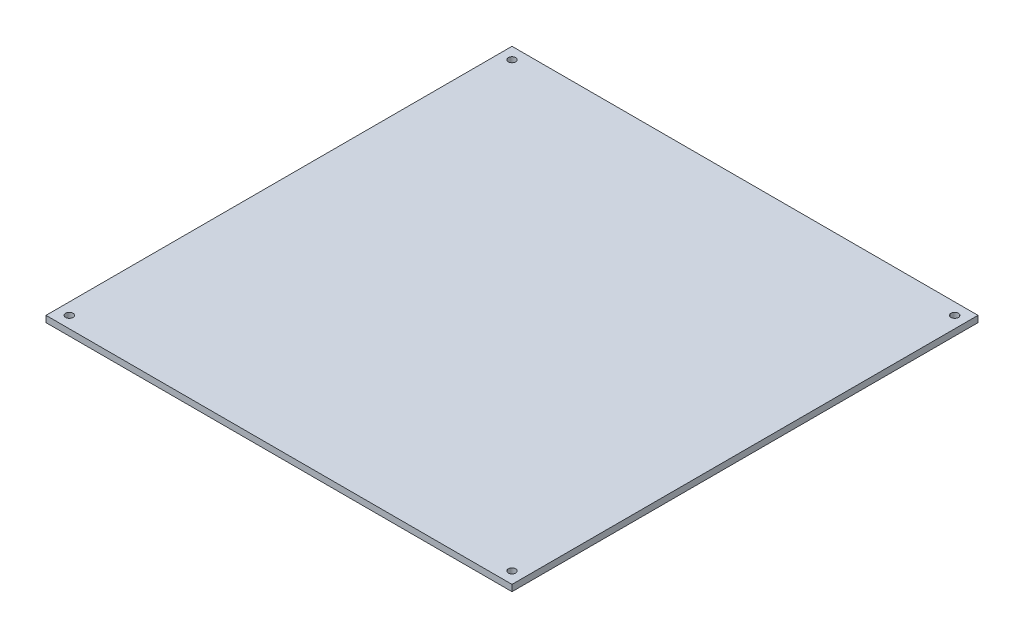
SolidWorks part; units mm, degrees
ref_plane "Front Plane" through (0, 0, 0) normal (0, 0, 1) x (1, 0, 0)
ref_plane "Top Plane" through (0, 0, 0) normal (0, 1, 0) x (1, 0, 0)
ref_plane "Right Plane" through (0, 0, 0) normal (1, 0, 0) x (0, 0, -1)
sketch "Sketch1" plane through (0, 0, 0) normal (0, 1, 0) x (1, 0, 0)
  line L0 (-110, 220) -> (-110, 0) construction
  line L1 (0, 0) -> (-220, 0)
  line L2 (0, 0) -> (0, 220)
  line L3 (0, 220) -> (-220, 220)
  line L4 (-220, 0) -> (-220, 220)
  line L5 (-220, 110) -> (0, 110) construction
  circle A0 centre (-214.5, 214.5) radius 1.75
  circle A1 centre (-5.5, 214.5) radius 1.75
  circle A2 centre (-5.5, 5.5) radius 1.75
  circle A3 centre (-214.5, 5.5) radius 1.75
  dimension "D3" = 3.5
  dimension "D1" = 5.5
  dimension "D2" = 5.5
  dimension "D4" = 220
  dimension "D5" = 220
extrude "Boss-Extrude1" add sketch "Sketch1" along normal blind 3
